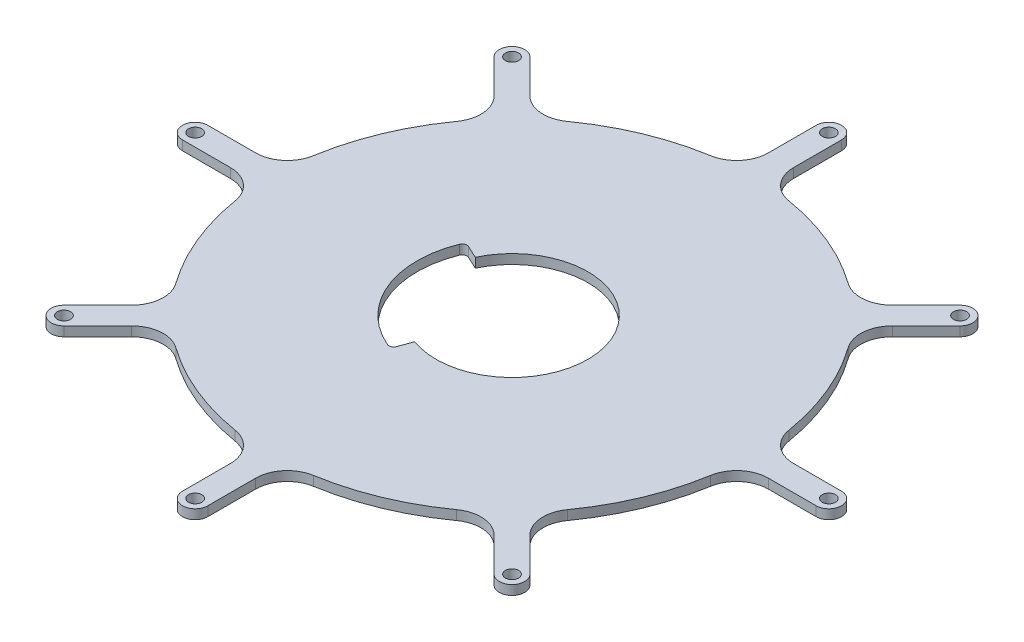
SolidWorks part; units mm, degrees
material "Thornel Mat VMA"
ref_plane "Front Plane" through (0, 0, 0) normal (0, 0, 1) x (1, 0, 0)
ref_plane "Top Plane" through (0, 0, 0) normal (0, 1, 0) x (1, 0, 0)
ref_plane "Right Plane" through (0, 0, 0) normal (1, 0, 0) x (0, 0, -1)
sketch "Sketch1" plane through (0, 0, 0) normal (0, 1, 0) x (1, 0, 0)
  line L0 (0, 0) -> (100.17, 0) construction
  line L1 (36.7402, 0) -> (100.17, 0) construction
  line L2 (36.7402, 4) -> (100.17, 4)
  line L3 (36.7402, -4) -> (100.17, -4)
  line L4 (25.9793, -25.9793) -> (70.8309, -70.8309) construction
  line L5 (28.8077, -23.1508) -> (73.6593, -68.0025)
  line L6 (23.1508, -28.8077) -> (68.0025, -73.6593)
  line L7 (0, -36.7402) -> (0, -100.17) construction
  line L8 (4, -36.7402) -> (4, -100.17)
  line L9 (-4, -36.7402) -> (-4, -100.17)
  line L10 (-25.9793, -25.9793) -> (-70.8309, -70.8309) construction
  line L11 (-23.1508, -28.8077) -> (-68.0025, -73.6593)
  line L12 (-28.8077, -23.1508) -> (-73.6593, -68.0025)
  line L13 (-36.7402, 0) -> (-100.17, 0) construction
  line L14 (-36.7402, -4) -> (-100.17, -4)
  line L15 (-36.7402, 4) -> (-100.17, 4)
  line L16 (-25.9793, 25.9793) -> (-70.8309, 70.8309) construction
  line L17 (-28.8077, 23.1508) -> (-73.6593, 68.0025)
  line L18 (-23.1508, 28.8077) -> (-68.0025, 73.6593)
  line L19 (0, 36.7402) -> (0, 100.17) construction
  line L20 (-4, 36.7402) -> (-4, 100.17)
  line L21 (4, 36.7402) -> (4, 100.17)
  line L22 (25.9793, 25.9793) -> (70.8309, 70.8309) construction
  line L23 (23.1508, 28.8077) -> (68.0025, 73.6593)
  line L24 (28.8077, 23.1508) -> (73.6593, 68.0025)
  circle A0 centre (0, 0) radius 76.17
  arc A1 (36.7402, 4) -> (36.7402, -4) centre (36.7402, 0) ccw
  arc A2 (100.17, -4) -> (100.17, 4) centre (100.17, 0) ccw
  arc A3 (28.8077, -23.1508) -> (23.1508, -28.8077) centre (25.9793, -25.9793) ccw
  arc A4 (68.0025, -73.6593) -> (73.6593, -68.0025) centre (70.8309, -70.8309) ccw
  arc A5 (4, -36.7402) -> (-4, -36.7402) centre (0, -36.7402) ccw
  arc A6 (-4, -100.17) -> (4, -100.17) centre (0, -100.17) ccw
  arc A7 (-23.1508, -28.8077) -> (-28.8077, -23.1508) centre (-25.9793, -25.9793) ccw
  arc A8 (-73.6593, -68.0025) -> (-68.0025, -73.6593) centre (-70.8309, -70.8309) ccw
  arc A9 (-36.7402, -4) -> (-36.7402, 4) centre (-36.7402, 0) ccw
  arc A10 (-100.17, 4) -> (-100.17, -4) centre (-100.17, 0) ccw
  arc A11 (-28.8077, 23.1508) -> (-23.1508, 28.8077) centre (-25.9793, 25.9793) ccw
  arc A12 (-68.0025, 73.6593) -> (-73.6593, 68.0025) centre (-70.8309, 70.8309) ccw
  arc A13 (-4, 36.7402) -> (4, 36.7402) centre (0, 36.7402) ccw
  arc A14 (4, 100.17) -> (-4, 100.17) centre (0, 100.17) ccw
  arc A15 (23.1508, 28.8077) -> (28.8077, 23.1508) centre (25.9793, 25.9793) ccw
  arc A16 (73.6593, 68.0025) -> (68.0025, 73.6593) centre (70.8309, 70.8309) ccw
  point P5 (68.4551, 0)
  point P14 (48.4051, -48.4051)
  point P21 (0, -68.4551)
  point P28 (-48.4051, -48.4051)
  point P35 (-68.4551, 0)
  point P42 (-48.4051, 48.4051)
  point P49 (0, 68.4551)
  point P56 (48.4051, 48.4051)
  point P61 (0, 0)
  dimension "D1" = 152.34
  dimension "D3" = 4
  dimension "D2" = 100.17
  dimension "D4" = 8
extrude "Boss-Extrude1" add sketch "Sketch1" along normal blind 3 contours A15 L23 A0 L21 A13 L20 L18 A11 L17 L15 A9 L14 L12 A7 L11 L9 A5 L8 L6 A3 L5 L3 A1 L2 L24 | L21 A14 L20 A0 | L20 A13 L21 A0 | L18 A12 L17 A0 | L17 A11 L18 A0 | L15 A10 L14 A0 | L14 A9 L15 A0 | L12 A8 L11 A0 | L11 A7 L12 A0 | L8 A5 L9 A0 | L9 A6 L8 A0 | L5 A3 L6 A0 | L6 A4 L5 A0 | L2 A1 L3 A0 | L3 A2 L2 A0 | L23 A15 L24 A0 | L24 A16 L23 A0
sketch "Sketch3" plane through (0, 3, 0) normal (0, 1, 0) x (1, 0, 0)
  circle A0 centre (0, 0) radius 100.17 construction
  circle A1 centre (100.17, 0) radius 2.1
  circle A2 centre (70.8309, -70.8309) radius 2.1
  circle A3 centre (0, -100.17) radius 2.1
  circle A4 centre (-70.8309, -70.8309) radius 2.1
  circle A5 centre (-100.17, 0) radius 2.1
  circle A6 centre (-70.8309, 70.8309) radius 2.1
  circle A7 centre (0, 100.17) radius 2.1
  circle A8 centre (70.8309, 70.8309) radius 2.1
  point P22 (0, 0)
  dimension "D1" = 4.2
  dimension "D2" = 8
extrude "Cut-Extrude1" cut sketch "Sketch3" against normal blind 5
fillet "Fillet1" radius 10 16 edges at (50.9576, 1.5, 56.6144) (-4, 1.5, 76.0649) (-56.6144, 1.5, 50.9576) (-76.0649, 1.5, 4) (-56.6144, 1.5, -50.9576) (-4, 1.5, -76.0649) (-76.0649, 1.5, -4) (-50.9576, 1.5, -56.6144) (50.9576, 1.5, -56.6144) (4, 1.5, -76.0649) (76.0649, 1.5, -4) (56.6144, 1.5, -50.9576) (76.0649, 1.5, 4) (56.6144, 1.5, 50.9576) (4, 1.5, 76.0649) (-50.9576, 1.5, 56.6144)
sketch "Sketch4" plane through (0, 3, 0) normal (0, 1, 0) x (1, 0, 0)
  line L0 (-25.794, 12.0279) -> (0, 0)
  line L1 (0, 0) -> (-9.7341, -26.7441)
  line L2 (-129.3744, 120) -> (-21.1317, 120) construction
  line L3 (-75.253, 65.8787) -> (-75.253, 174.1214) construction
  circle A0 centre (0, 0) radius 24
  arc A1 (-27.8188, 11.23) -> (-11.7301, -27.6117) centre (0, 0) ccw
  arc A2 (-9.7341, -26.7441) -> (-11.7301, -27.6117) centre (-11.1436, -26.2311) cw
  arc A3 (-25.794, 12.0279) -> (-27.8188, 11.23) centre (-26.4279, 10.6685) ccw
  dimension "D1" = 48
  dimension "D2" = 30
  dimension "D5" = 1.5
  dimension "D3" = 25
  dimension "D4" = 20
extrude "Cut-Extrude2" cut sketch "Sketch4" against normal blind 10 contours L0 A3 A1 A2 L1 A0 | L0 A0 L1 | L1 A0 L0
